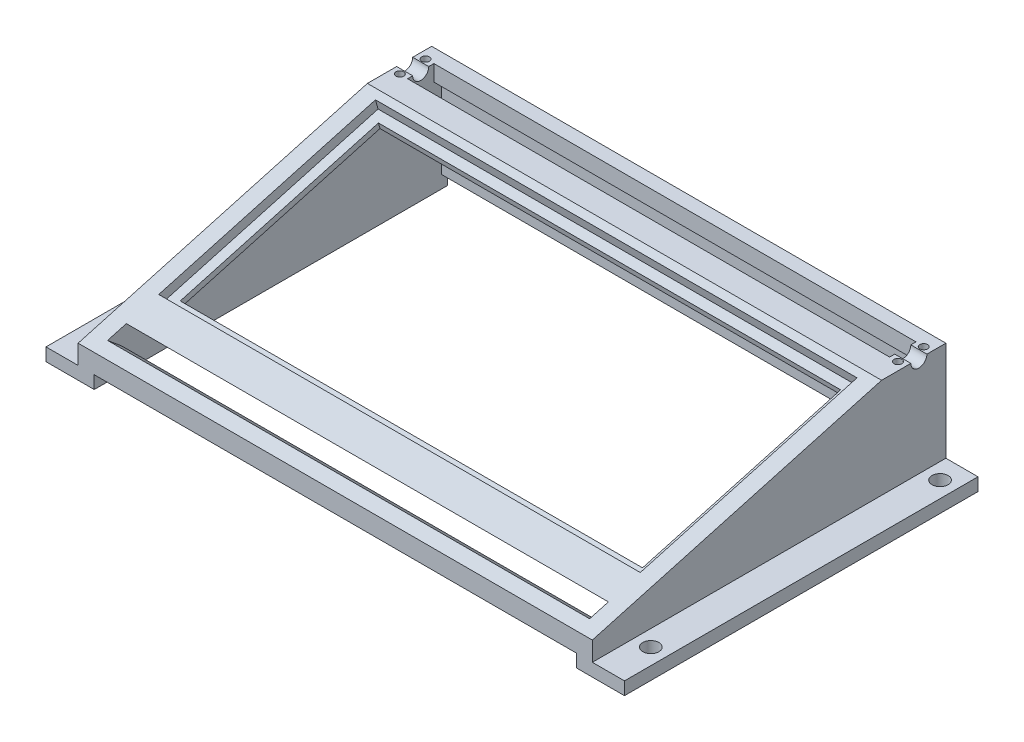
SolidWorks part; units mm, degrees
material "ABS PC"
ref_plane "Front Plane" through (0, 0, 0) normal (0, 0, 1) x (1, 0, 0)
ref_plane "Top Plane" through (0, 0, 0) normal (0, 1, 0) x (1, 0, 0)
ref_plane "Right Plane" through (0, 0, 0) normal (1, 0, 0) x (0, 0, -1)
sketch "Sketch1" plane through (0, 0, 0) normal (0, 0, 1) x (1, 0, 0)
  line L1 (101.6, 0) -> (101.6, 12.7)
  line L2 (101.6, 12.7) -> (-101.6, 12.7)
  line L3 (-101.6, 12.7) -> (-101.6, 0)
  line L4 (101.6, 0) -> (95.25, 0)
  line L5 (95.25, 0) -> (95.25, 6.35)
  line L6 (95.25, 6.35) -> (-95.25, 6.35)
  line L7 (-95.25, 6.35) -> (-95.25, 0)
  line L8 (-95.25, 0) -> (-101.6, 0)
  point P4 (0, 0)
  point P12 (0, 12.7)
  dimension "D1" = 190.5
  dimension "D2" = 203.2
  dimension "D3" = 12.7
  dimension "D4" = 6.35
ref_plane "Plane1" through (0, 0, -114.3) normal (0, 0, 1) x (1, 0, 0)
sketch "Sketch2" plane through (0, 0, -114.3) normal (0, 0, 1) x (1, 0, 0)
  line L0 (-95.25, 0) -> (-95.25, 38.1)
  line L1 (-95.25, 38.1) -> (95.25, 38.1)
  line L2 (95.25, 38.1) -> (95.25, 0)
  line L3 (95.25, 0) -> (101.6, 0)
  line L4 (101.6, 0) -> (101.6, 44.45)
  line L5 (101.6, 44.45) -> (-101.6, 44.45)
  line L6 (-101.6, 44.45) -> (-101.6, 0)
  line L7 (-101.6, 0) -> (-95.25, 0)
  dimension "D1" = 44.45
  dimension "D2" = 6.35
loft "Loft1" add profiles "Sketch1", "Sketch2"
sketch "Sketch4" plane through (101.6, 0, 0) normal (1, 0, 0) x (0, 0, -1)
  line L8 (21.4872, 43.8072) -> (21.4872, 2.9322) construction
  line L9 (12.7, 32.7373) -> (5.2781, 32.7373)
  line L10 (12.7, 16.2278) -> (12.7, 32.7373)
  line L11 (19.6543, 10.3924) -> (12.7, 16.2278)
  line L12 (15.5499, 5.5471) -> (19.6543, 10.3924)
  line L13 (5.2781, 14.1661) -> (15.5499, 5.5471)
  line L14 (5.2781, 32.7373) -> (5.2781, 14.1661)
  line L15 (0, 12.7) -> (114.3, 44.45) construction
  line L17 (114.3, 0) -> (114.3, 44.45) construction
  dimension "D1" = 6.35
  dimension "D2" = 130
  dimension "D3" = 101.6
extrude "Cut-Extrude1" cut sketch "Sketch4" against normal up to surface (190.5 mm away) from surface at -6.35 up to face at (-95.25, 1.5875, -28.575) starting at face at (95.25, 12.7, -28.575)
sketch "Sketch7" plane through (95.25, 0, 0) normal (-1, 0, 0) x (0, 0, 1)
  line L0 (0, 0) -> (-114.3, 0) construction
  line L1 (0, 6.35) -> (-2.4473, 7.0298)
  line L2 (0, 6.35) -> (0, 5.08)
  line L3 (0, 5.08) -> (-2.4473, 5.08)
  line L4 (-2.4473, 7.0298) -> (-2.4473, 5.08)
  line L5 (0, 6.35) -> (-10.9636, 9.3954) construction
  dimension "D1" = 2.54
  dimension "D2" = 5.08
extrude "Boss-Extrude4" add sketch "Sketch7" along normal up to surface (190.5 mm away)
sketch "Sketch9" plane through (0, 0, -114.3) normal (0, 0, -1) x (-1, 0, 0)
  line L0 (-95.25, 0) -> (-101.6, 0)
  line L1 (-101.6, 0) -> (-101.6, 44.45)
  line L2 (-101.6, 44.45) -> (101.6, 44.45)
  line L3 (101.6, 44.45) -> (101.6, 0)
  line L4 (101.6, 0) -> (95.25, 0)
  line L5 (95.25, 0) -> (95.25, 38.1)
  line L6 (95.25, 38.1) -> (-95.25, 38.1)
  line L7 (-95.25, 38.1) -> (-95.25, 0)
extrude "Boss-Extrude5" add sketch "Sketch9" along normal blind 25.4
sketch "Sketch3" plane through (0, 0, 0) normal (1, 0, 0) x (0, 0, -1)
  line L0 (139.7, 44.45) -> (139.7, 5.08)
  line L1 (139.7, 5.08) -> (137.16, 5.08)
  line L2 (139.7, 0) -> (139.7, 44.45) construction
  line L3 (137.16, 5.08) -> (137.16, 44.45)
  line L5 (137.16, 44.45) -> (139.7, 44.45)
  line L6 (0, 0) -> (139.7, 0) construction
  line L7 (139.7, 44.45) -> (114.3, 44.45) construction
  dimension "D1" = 2.54
  dimension "D2" = 5.08
extrude "Boss-Extrude1" add sketch "Sketch3" along normal mid plane 190.5
sketch "Sketch11" plane through (-101.6, 0, 0) normal (-1, 0, 0) x (0, 0, 1)
  line L0 (-139.7, 44.45) -> (-114.3, 44.45) construction
  circle A0 centre (-129.032, 44.45) radius 3.175
  dimension "D1" = 6.35
  dimension "D2" = 10.668
extrude "Cut-Extrude6" cut sketch "Sketch11" against normal through all
sketch "Sketch12" plane through (0, 44.45, 0) normal (0, 1, 0) x (1, 0, 0)
  line L1 (101.6, 129.032) -> (-137.298, 129.032) construction
  line L2 (101.6, 125.857) -> (101.6, 132.207) construction
  line L3 (0, 139.7) -> (0, 104.093) construction
  line L4 (-101.6, 139.7) -> (101.6, 139.7) construction
  circle A0 centre (98.425, 123.952) radius 1.524
  circle A1 centre (98.425, 134.112) radius 1.524
  circle A2 centre (-98.425, 134.112) radius 1.524
  circle A3 centre (-98.425, 123.952) radius 1.524
  dimension "D1" = 3.048
  dimension "D2" = 5.08
extrude "Cut-Extrude7" cut sketch "Sketch12" against normal blind 10.16
sketch "Sketch5" plane through (0, 11.7903, 3.2751) normal (0, 0.9635, 0.2676) x (1, 0, 0)
  line L1 (-95.25, 118.7663) -> (95.0415, 118.7663)
  line L2 (-95.25, 118.7663) -> (-95.25, 29.8663)
  line L3 (-95.25, 29.8663) -> (95.0415, 29.8663)
  line L4 (95.0415, 118.7663) -> (95.0415, 29.8663)
  line L5 (-95.25, 8.877) -> (-95.25, 16.5799) construction
  dimension "D1" = 88.9
extrude "Cut-Extrude2" cut sketch "Sketch5" against normal blind 3.81
sketch "Sketch6" plane through (0, 8.1193, 2.2553) normal (0, 0.9635, 0.2676) x (1, 0, 0)
  line L0 (-95.25, 118.7663) -> (-95.25, 29.8663) construction
  line L1 (-91.44, 114.9563) -> (91.2315, 114.9563)
  line L2 (-91.44, 114.9563) -> (-91.44, 33.6763)
  line L3 (-91.44, 33.6763) -> (91.2315, 33.6763)
  line L4 (91.2315, 114.9563) -> (91.2315, 33.6763)
  line L5 (-95.25, 29.8663) -> (95.0415, 29.8663) construction
  line L6 (95.0415, 118.7663) -> (-95.25, 118.7663) construction
  line L7 (95.0415, 29.8663) -> (95.0415, 118.7663) construction
  dimension "D1" = 3.81
  dimension "D2" = 3.81
  dimension "D3" = 3.81
  dimension "D4" = 3.81
extrude "Cut-Extrude3" cut sketch "Sketch6" against normal blind 12.7
sketch "Sketch14" plane through (0, 44.45, 0) normal (0, 1, 0) x (1, 0, 0)
  line L0 (-101.6, 125.857) -> (-101.6, 114.3) construction
  line L1 (-95.25, 123.825) -> (95.25, 123.825)
  line L2 (-95.25, 123.825) -> (-95.25, 134.239)
  line L3 (-95.25, 134.239) -> (95.25, 134.239)
  line L4 (95.25, 123.825) -> (95.25, 134.239)
  line L5 (-95.25, 123.825) -> (95.25, 134.239) construction
  line L6 (-95.25, 134.239) -> (95.25, 123.825) construction
  line L7 (101.6, 125.857) -> (101.6, 114.3) construction
  line L8 (-101.6, 129.032) -> (101.6, 129.032) construction
  line L9 (-101.6, 132.207) -> (-101.6, 125.857) construction
  line L10 (101.6, 125.857) -> (101.6, 132.207) construction
  point P0 (0, 129.032)
  point P15 (-95.25, 129.032)
  dimension "D1" = 10.414
  dimension "D2" = 6.35
  dimension "D3" = 6.35
extrude "Cut-Extrude8" cut sketch "Sketch14" against normal through all
sketch "Sketch15" plane through (101.6, 0, 0) normal (1, 0, 0) x (0, 0, -1)
  line L0 (139.7, 44.45) -> (139.7, 0) construction
  line L1 (0, 0) -> (139.7, 0)
  line L2 (0, 0) -> (0, 5.08)
  line L3 (0, 5.08) -> (139.7, 5.08)
  line L4 (139.7, 0) -> (139.7, 5.08)
  dimension "D1" = 5.08
extrude "Boss-Extrude6" add sketch "Sketch15" along normal blind 12.7
sketch "Sketch16" plane through (0, 5.08, 0) normal (0, 1, 0) x (1, 0, 0)
  line L0 (107.95, 139.7) -> (107.95, 0) construction
  line L1 (114.3, 139.7) -> (101.6, 139.7) construction
  line L2 (114.3, 0) -> (101.6, 0) construction
hole_wizard "1/4 (0.25) Diameter Hole1" positions "Sketch17" profile "Sketch18" hole size "1/4" standard "ANSI Inch" end condition through all
sketch "Sketch17" plane through (0, 5.08, 0) normal (0, 1, 0) x (1, 0, 0)
  line L0 (107.95, 139.7) -> (107.95, 0) construction
  point P0 (107.95, 16.7573)
  point P4 (107.95, 131.0573)
  point P9 (0, 0)
  dimension "D1" = 114.3
sketch "Sketch18" plane through (107.95, 5.08, -16.7573) normal (1, 0, 0) x (0, 0, 1)
  line L0 (0, 0) -> (0, 5.0801)
  line L1 (0, 5.0801) -> (3.175, 5.0801)
  line L2 (3.175, 5.0801) -> (3.175, 0)
  line L5 (3.175, 0) -> (0, 0)
  line L11 (0, -6.35) -> (0, 107.95) construction
  dimension "Thru Hole Dia." = 6.35
  dimension "Thru Hole Depth" = 5.0801
mirror "Mirror1" about plane through (0, 0, 0) normal (1, 0, 0) of "Boss-Extrude6"
mirror "Mirror2" about plane through (0, 0, 0) normal (1, 0, 0) of "1/4 (0.25) Diameter Hole1"
